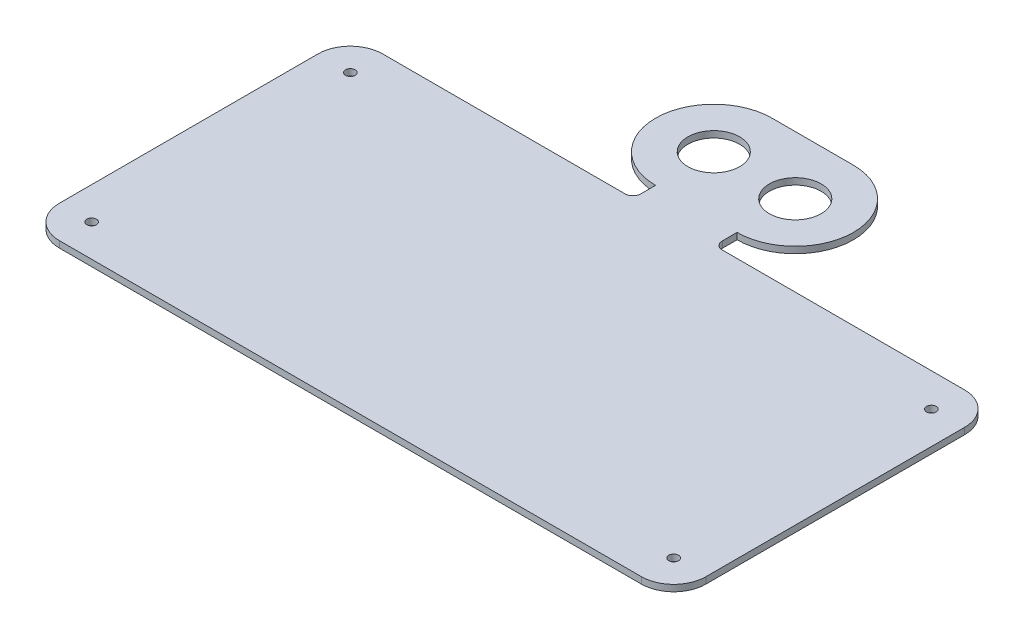
SolidWorks part; units mm, degrees
ref_plane "Front Plane" through (0, 0, 0) normal (0, 0, 1) x (1, 0, 0)
ref_plane "Top Plane" through (0, 0, 0) normal (0, 1, 0) x (1, 0, 0)
ref_plane "Right Plane" through (0, 0, 0) normal (1, 0, 0) x (0, 0, -1)
sketch "Sketch1" plane through (0, 0, 0) normal (0, 1, 0) x (1, 0, 0)
  line L0 (-52.8928, 52.91) -> (-52.8928, 24.16)
  line L1 (-42.8928, -37.09) -> (137.1024, -37.09)
  line L2 (147.1024, 52.91) -> (147.1024, 24.16)
  line L7 (-52.8928, 1.66) -> (-52.8928, -27.09)
  line L12 (147.1024, 1.66) -> (147.1024, -27.09)
  line L13 (-42.8928, 62.91) -> (32.3517, 62.91)
  line L14 (61.7316, 62.91) -> (137.1024, 62.91)
  line L15 (34.5048, 105.91) -> (59.928, 105.9093)
  line L16 (-52.8928, 24.16) -> (-52.8928, 1.66)
  line L17 (34.5048, 69.91) -> (34.5048, 65.3745)
  line L20 (59.7053, 69.9107) -> (59.7053, 65.3752)
  line L21 (147.1024, 24.16) -> (147.1024, 1.66)
  arc A0 (-52.8928, -27.09) -> (-42.8928, -37.09) centre (-42.8928, -27.09) ccw
  arc A1 (137.1024, -37.09) -> (147.1024, -27.09) centre (137.1024, -27.09) ccw
  arc A2 (137.1024, 62.91) -> (147.1024, 52.91) centre (137.1024, 52.91) cw
  arc A3 (-42.8928, 62.91) -> (-52.8928, 52.91) centre (-42.8928, 52.91) ccw
  circle A4 centre (59.7053, 87.9107) radius 8
  circle A5 centre (34.5048, 87.91) radius 8
  arc A9 (59.7053, 69.9107) -> (59.4836, 105.9093) centre (59.7053, 87.9107) ccw
  arc A10 (34.5048, 65.3745) -> (32.3517, 62.91) centre (32.0178, 65.3745) cw
  arc A11 (59.7053, 65.3752) -> (62.2171, 62.8627) centre (62.2171, 65.3744) ccw
  circle A12 centre (-42.8928, 52.91) radius 1.5
  circle A13 centre (59.7053, 87.9107) radius 18 construction
  circle A14 centre (-42.8928, -27.09) radius 1.5
  arc A15 (34.5058, 105.91) -> (34.5048, 69.91) centre (34.5048, 87.91) ccw
  circle A16 centre (137.1024, -27.09) radius 1.5
  circle A17 centre (137.1024, 52.6129) radius 1.5
  dimension "D2" = 10
extrude "Boss-Extrude6" add sketch "Sketch1" along normal blind 2
